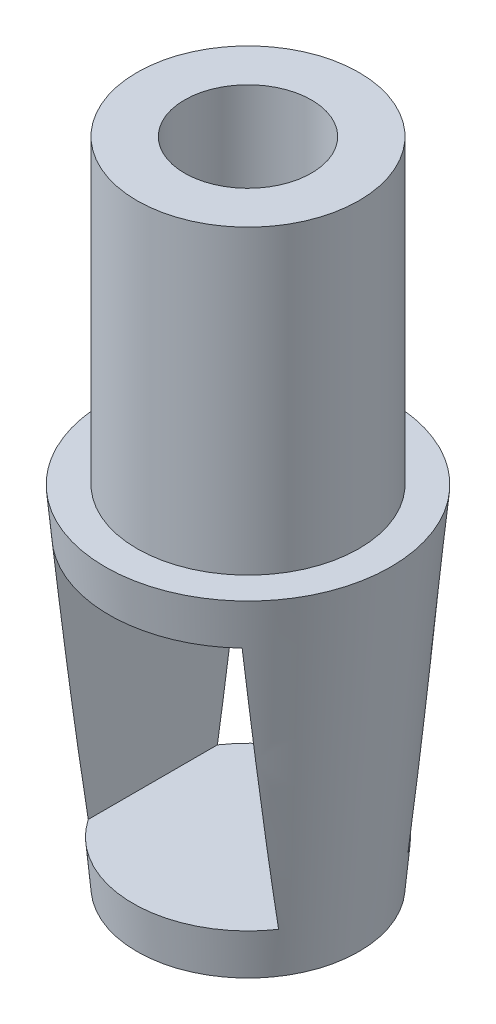
SolidWorks part; units mm, degrees
ref_plane "Front Plane" through (0, 0, 0) normal (0, 0, 1) x (1, 0, 0)
ref_plane "Top Plane" through (0, 0, 0) normal (0, 1, 0) x (1, 0, 0)
ref_plane "Right Plane" through (0, 0, 0) normal (1, 0, 0) x (0, 0, -1)
sketch "Sketch2" plane through (0, 0, 0) normal (0, 0, 1) x (1, 0, 0)
  line L0 (0, 0) -> (9, 0)
  line L1 (0, 0) -> (0, -22)
  line L2 (0, -22) -> (7, -22)
  line L3 (7, -22) -> (9, 0)
revolve "Revolve2" add sketch "Sketch2" angle 360 about L1
sketch "Sketch3" plane through (0, 0, 0) normal (0, 1, 0) x (1, 0, 0)
  circle A0 centre (0, 0) radius 7
extrude "Boss-Extrude1" add sketch "Sketch3" along normal blind 19
sketch "Sketch4" plane through (0, 19, 0) normal (0, 1, 0) x (1, 0, 0)
  circle A0 centre (0, 0) radius 4
extrude "Cut-Extrude1" cut sketch "Sketch4" against normal blind 19
sketch "Sketch5" plane through (0, 0, 0) normal (0, 0, 1) x (1, 0, 0)
  line L10 (-6, -2.75) -> (6, -2.75)
  line L11 (-6, -2.75) -> (-6, -19.25)
  line L12 (-6, -19.25) -> (6, -19.25)
  line L13 (6, -2.75) -> (6, -19.25)
  point P11 (0, -11)
  dimension "D1" = 16.5
  dimension "D2" = 12
extrude "Cut-Extrude2" cut sketch "Sketch5" against normal through all and the other way through all
